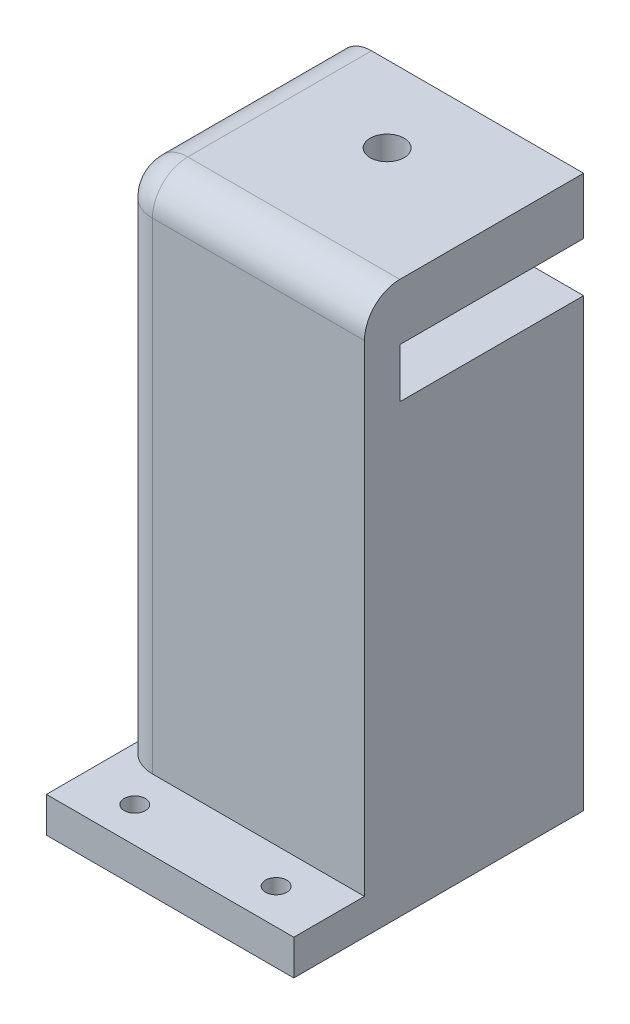
SolidWorks part; units mm, degrees
ref_plane "Front Plane" through (0, 0, 0) normal (0, 0, 1) x (1, 0, 0)
ref_plane "Top Plane" through (0, 0, 0) normal (0, 1, 0) x (1, 0, 0)
ref_plane "Right Plane" through (0, 0, 0) normal (1, 0, 0) x (0, 0, -1)
sketch "Sketch1" plane through (0, 0, 0) normal (0, 1, 0) x (1, 0, 0)
  line L1 (0, 0) -> (35, 0)
  line L2 (0, 0) -> (0, 41)
  line L3 (0, 41) -> (35, 41)
  line L4 (35, 0) -> (35, 41)
  dimension "D1" = 41
  dimension "D2" = 35
extrude "Boss-Extrude1" add sketch "Sketch1" along normal blind 5
sketch "Sketch2" plane through (0, 5, 0) normal (0, 1, 0) x (1, 0, 0)
  line L0 (0, 0) -> (35, 0) construction
  line L1 (0, 41) -> (0, 0) construction
  line L2 (35, 0) -> (35, 41) construction
  circle A0 centre (7.5, 5) radius 1.5
  circle A1 centre (27.5, 5) radius 1.5
  dimension "D1" = 5
  dimension "D3" = 5
  dimension "D2" = 7.5
  dimension "D4" = 7.5
extrude "Cut-Extrude1" cut sketch "Sketch2" against normal blind 5
sketch "Sketch3" plane through (0, 5, 0) normal (0, 1, 0) x (1, 0, 0)
  line L0 (35, 0) -> (35, 41) construction
  line L1 (0, 41) -> (35, 41)
  line L2 (0, 41) -> (0, 10)
  line L3 (0, 10) -> (35, 10)
  line L4 (35, 41) -> (35, 10)
  line L5 (0, 0) -> (35, 0) construction
  dimension "D1" = 10
extrude "Boss-Extrude2" add sketch "Sketch3" along normal blind 73.1
sketch "Sketch4" plane through (35, 0, 0) normal (1, 0, 0) x (0, 0, -1)
  line L0 (41, 78.1) -> (41, 0) construction
  line L1 (15, 70.1) -> (41, 70.1)
  line L2 (15, 70.1) -> (15, 63.1)
  line L3 (15, 63.1) -> (41, 63.1)
  line L4 (41, 70.1) -> (41, 63.1)
  line L5 (0, 0) -> (41, 0) construction
  dimension "D1" = 7
  dimension "D2" = 63.1
  dimension "D3" = 26
extrude "Cut-Extrude2" cut sketch "Sketch4" against normal blind 30
sketch "Sketch5" plane through (0, 78.1, 0) normal (0, 1, 0) x (1, 0, 0)
  line L0 (0, 41) -> (0, 10) construction
  circle A0 centre (18, 30.2021) radius 2.4
  dimension "D1" = 18
extrude "Cut-Extrude3" cut sketch "Sketch5" against normal blind 8
fillet "Fillet1" radius 5 1 edges at (0, 78.1, -25.5)
fillet "Fillet2" radius 5 3 edges at (0, 39.05, -10) (1.4645, 76.6355, -10) (20, 78.1, -10)
